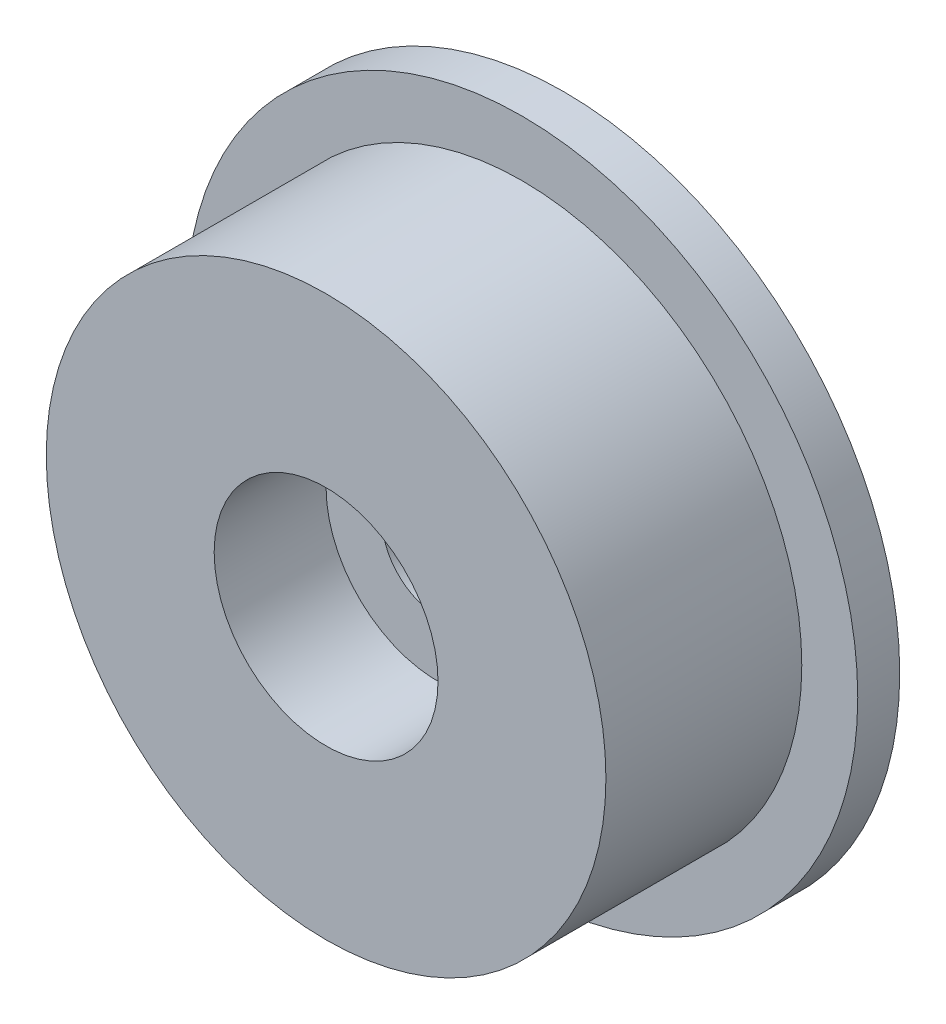
SolidWorks part; units mm, degrees
ref_plane "前视基准面" through (0, 0, 0) normal (0, 0, 1) x (1, 0, 0)
ref_plane "上视基准面" through (0, 0, 0) normal (0, 1, 0) x (1, 0, 0)
ref_plane "右视基准面" through (0, 0, 0) normal (1, 0, 0) x (0, 0, -1)
sketch "草图1" plane through (0, 0, 0) normal (0, 0, 1) x (1, 0, 0)
  circle A0 centre (0, 0) radius 12
  dimension "D1" = 24
extrude "凸台-拉伸1" add sketch "草图1" along normal blind 1.5 contours A0
sketch "草图2" plane through (0, 0, 1.5) normal (0, 0, 1) x (1, 0, 0)
  circle A0 centre (0, 0) radius 10
  dimension "D1" = 20
extrude "凸台-拉伸2" add sketch "草图2" along normal blind 7
sketch "草图3" plane through (0, 0, 0) normal (0, 0, -1) x (-1, 0, 0)
  circle A0 centre (0, 0) radius 2
extrude "切除-拉伸1" cut sketch "草图3" against normal blind 27
sketch "草图4" plane through (0, 0, 8.5) normal (0, 0, 1) x (1, 0, 0)
  circle A0 centre (0, 0) radius 4
  dimension "D1" = 8
extrude "切除-拉伸2" cut sketch "草图4" against normal blind 4
